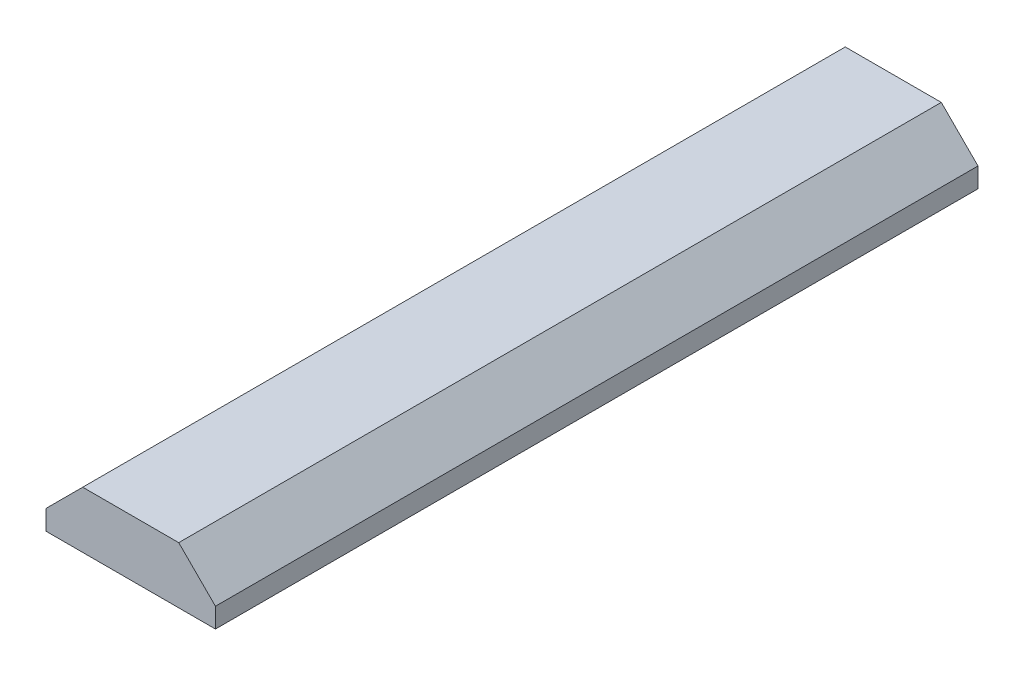
SolidWorks part; units mm, degrees
ref_plane "Ebene vorne" through (0, 0, 0) normal (0, 0, 1) x (1, 0, 0)
ref_plane "Ebene oben" through (0, 0, 0) normal (0, 1, 0) x (1, 0, 0)
ref_plane "Ebene rechts" through (0, 0, 0) normal (1, 0, 0) x (0, 0, -1)
sketch "Skizze1" plane through (0, 0, 0) normal (0, 0, 1) x (1, 0, 0)
  line L0 (0, 0) -> (0, 23680.6173) construction
  line L1 (3.4, 1.8089) -> (-3.4, 1.8089)
  line L2 (-3.4, 1.8089) -> (-6, -0.7911)
  line L3 (-6, -0.7911) -> (-6, -2.1911)
  line L4 (-6, -2.1911) -> (6, -2.1911)
  line L5 (6, -0.7911) -> (6, -2.1911)
  line L6 (3.4, 1.8089) -> (6, -0.7911)
  point P9 (0, -2.1911)
  point P11 (0, 1.8089)
  dimension "D1" = 3.4
  dimension "D2" = 6
  dimension "D3" = 4
  dimension "D4" = 135
extrude "Aufsatz-Linear austragen1" add sketch "Skizze1" along normal blind 54 contours L1 L2 L3 L4 L5 L6
